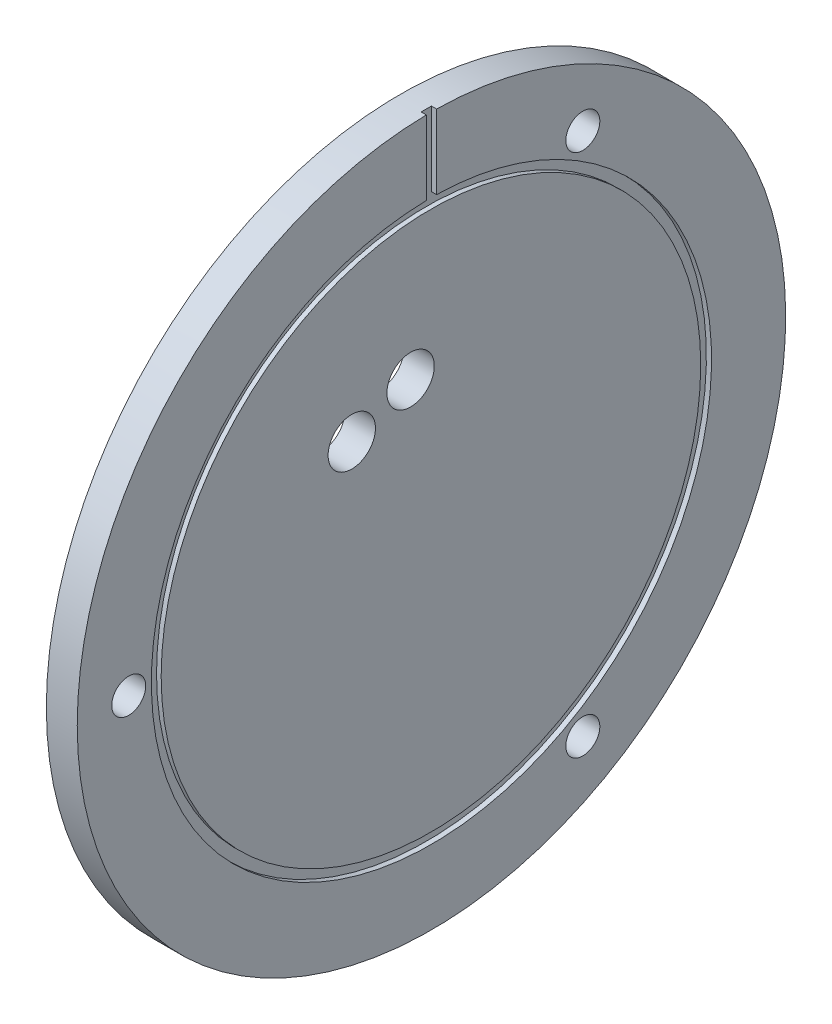
SolidWorks part; units mm, degrees
material "Copper"
ref_plane "Front Plane" through (0, 0, 0) normal (0, 0, 1) x (1, 0, 0)
ref_plane "Top Plane" through (0, 0, 0) normal (0, 1, 0) x (1, 0, 0)
ref_plane "Right Plane" through (0, 0, 0) normal (1, 0, 0) x (0, 0, -1)
sketch "Axial profile (mm)" plane through (0, 0, 0) normal (0, 0, 1) x (1, 0, 0)
  line L0 (-110, 0) -> (75, 0) construction
  line L1 (156.7, 0) -> (159.65, 0)
  line L2 (159.65, 0) -> (159.65, 26.2)
  line L3 (159.65, 26.2) -> (159.2, 26.2)
  line L4 (159.2, 26.2) -> (159.2, 27.2)
  line L5 (159.2, 27.2) -> (159.7, 27.2)
  line L6 (159.7, 27.2) -> (159.7, 34.4)
  line L7 (159.7, 34.4) -> (156.7, 34.4)
  line L8 (156.7, 34.4) -> (156.7, 0)
revolve "Full revolution" add sketch "Axial profile (mm)" angle 360 about L0
sketch "Sketch2" plane through (0, 0, 0) normal (1, 0, 0) x (0, 0, -1)
  circle A0 centre (-1.9774, 12.8487) radius 2.3
  circle A1 centre (-7.6872, 10.4836) radius 2.3
  circle A2 centre (-29.4, 0) radius 1.65
  circle A3 centre (14.7, -25.4611) radius 1.65
  circle A4 centre (14.7, 25.4611) radius 1.65
extrude "Axial holes" cut sketch "Sketch2" along normal through all and the other way through all
sketch "Sketch3" plane through (0, 0, 0) normal (1, 0, 0) x (0, 0, -1)
  line L0 (0.5, 26.2) -> (0.5, 35)
  line L1 (0.5, 35) -> (-0.5, 35)
  line L2 (-0.5, 35) -> (-0.5, 26.2)
  line L3 (-0.5, 26.2) -> (0.5, 26.2)
extrude "Dry interface vent - NOT a coolant passage" cut sketch "Sketch3" along normal blind 0.5 from offset 159.2
